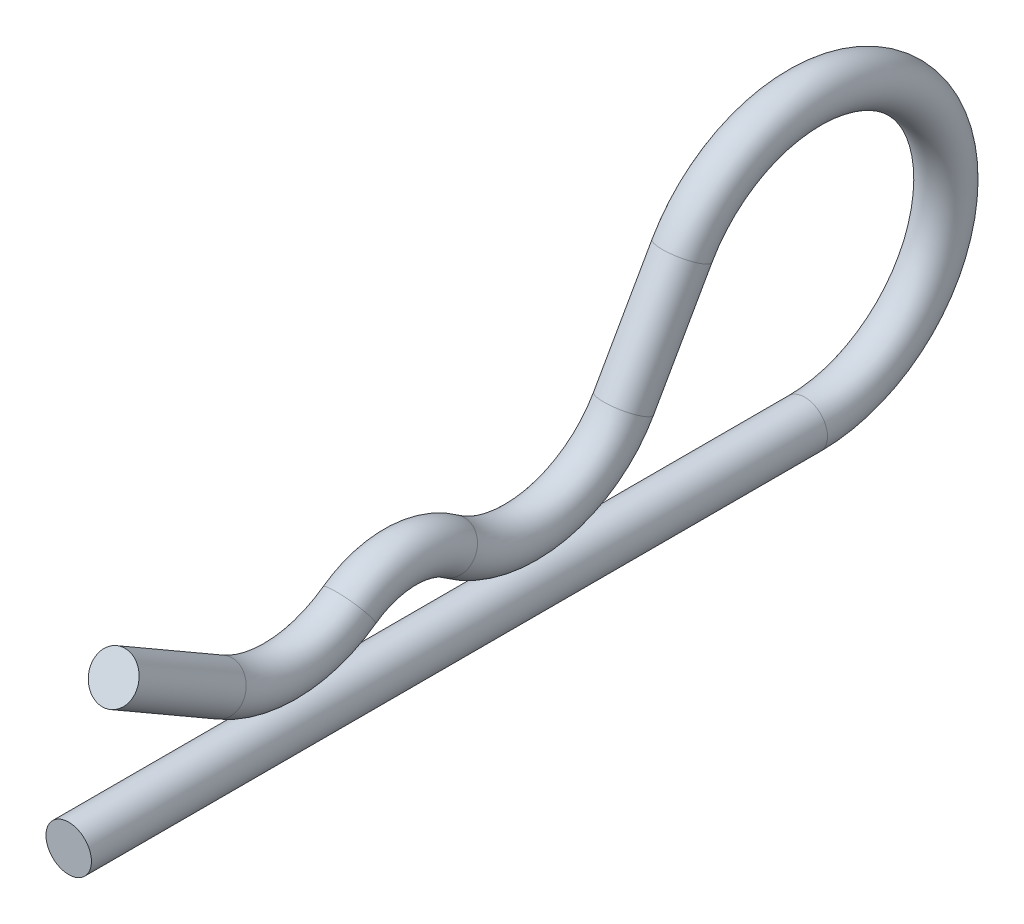
SolidWorks part; units mm, degrees
ref_plane "Front" through (0, 0, 0) normal (0, 0, 1) x (1, 0, 0)
ref_plane "Top" through (0, 0, 0) normal (0, 1, 0) x (1, 0, 0)
ref_plane "Right" through (0, 0, 0) normal (1, 0, 0) x (0, 0, -1)
sketch "Sketch1" plane through (0, 0, 0) normal (1, 0, 0) x (0, 0, -1)
  line L0 (-24.6697, 0) -> (24.6697, 0) construction
  line L1 (-10.5088, 1.524) -> (-10.5088, 4.8768) construction
  line L2 (35.6553, 0) -> (35.6552, 9.4615) construction
  line L3 (35.6552, 9.4615) -> (34.1312, 9.4615) construction
  line L4 (-24.6697, 0) -> (-24.6697, 1.524) construction
  line L5 (35.6553, 0) -> (-24.6697, 0) construction
  line L6 (-14.4776, 4.2638) -> (-21.6535, 8.4068) construction
  line L7 (-2.4447, 5.8132) -> (-2.4447, 0) construction
  line L8 (-24.6697, 0) -> (-24.6697, -1.524) construction
  line L13 (16.4391, 14.128) -> (12.5242, 7.2231) construction
  circle A0 centre (24.6697, 9.4615) radius 7.9375 construction
  arc A1 (0.9644, 4.7086) -> (-5.8539, 4.7086) centre (-2.4447, 0) ccw construction
  arc A6 (-5.8539, 4.7086) -> (-14.4776, 4.2638) centre (-10.5088, 11.1379) cw construction
  arc A8 (12.5242, 7.2231) -> (0.9644, 4.7086) centre (5.6193, 11.1379) cw construction
  arc A9 (24.6697, 0) -> (16.4391, 14.128) centre (24.6697, 9.4615) ccw construction
  point P2 (0, 0)
  point P5 (-10.5088, 3.2004)
  point P16 (-10.5088, 3.2004)
  dimension "D1" = 7.9375
  dimension "Eye Diameter" = 15.875
  dimension "D5" = 3.0163
  dimension "D9" = 30
  dimension "D11" = 1.524
  dimension "D3" = 1.524
  dimension "Length" = 60.325
  dimension "Wire Diameter" = 3.048
  dimension "D4" = 7.9375
  dimension "D6" = 3.3528
  dimension "D2" = 22.225
ref_plane "Plane1" through (0, 0, 24.6697) normal (0, 0, 1) x (1, 0, 0)
sketch "Sketch2" plane through (0, 0, 24.6697) normal (0, 0, 1) x (1, 0, 0)
  circle A0 centre (0, 0) radius 1.524
sketch "Sketch3" plane through (0, 0, 0) normal (1, 0, 0) x (0, 0, -1)
  line L0 (-14.4776, 4.2638) -> (-21.6535, 8.4068) construction
  line L1 (16.4391, 14.128) -> (12.5242, 7.2231) construction
  line L2 (-24.6697, 0) -> (24.6697, 0) construction
  line L3 (-14.4776, 4.2638) -> (-21.6535, 8.4068)
  line L4 (16.4391, 14.128) -> (12.5242, 7.2231)
  line L5 (-24.6697, 0) -> (24.6697, 0)
  arc A0 (-14.4776, 4.2638) -> (-5.8539, 4.7086) centre (-10.5088, 11.1379) ccw construction
  arc A1 (0.9644, 4.7086) -> (-5.8539, 4.7086) centre (-2.4447, 0) ccw construction
  arc A2 (0.9644, 4.7086) -> (12.5242, 7.2231) centre (5.6193, 11.1379) ccw construction
  arc A3 (24.6697, 0) -> (16.4391, 14.128) centre (24.6697, 9.4615) ccw construction
  arc A4 (-14.4776, 4.2638) -> (-5.8539, 4.7086) centre (-10.5088, 11.1379) ccw
  arc A5 (0.9644, 4.7086) -> (-5.8539, 4.7086) centre (-2.4447, 0) ccw
  arc A6 (0.9644, 4.7086) -> (12.5242, 7.2231) centre (5.6193, 11.1379) ccw
  arc A7 (24.6697, 0) -> (16.4391, 14.128) centre (24.6697, 9.4615) ccw
sweep "Sweep1" add profiles "Sketch2" path "Sketch3"
equation "\"D11@Sketch1\" = \"Wire Diameter@Sketch1\" / 2"
equation "\"D1@Sketch1\"=\"Eye Diameter@Sketch1\" / 2"
equation "\"D3@Sketch1\" = \"D11@Sketch1\""
equation "\"D5@Sketch1\" = \"Length@Sketch1\" * .05"
equation "\"D4@Sketch1\"=\"Eye Diameter@Sketch1\"/2"
equation "\"D6@Sketch1\"=\"Wire Diameter@Sketch1\"*1.1"
equation "\"D2@Sketch1\"=( \"Length@Sketch1\" - \"Eye Diameter@Sketch1\" )  / 2"
